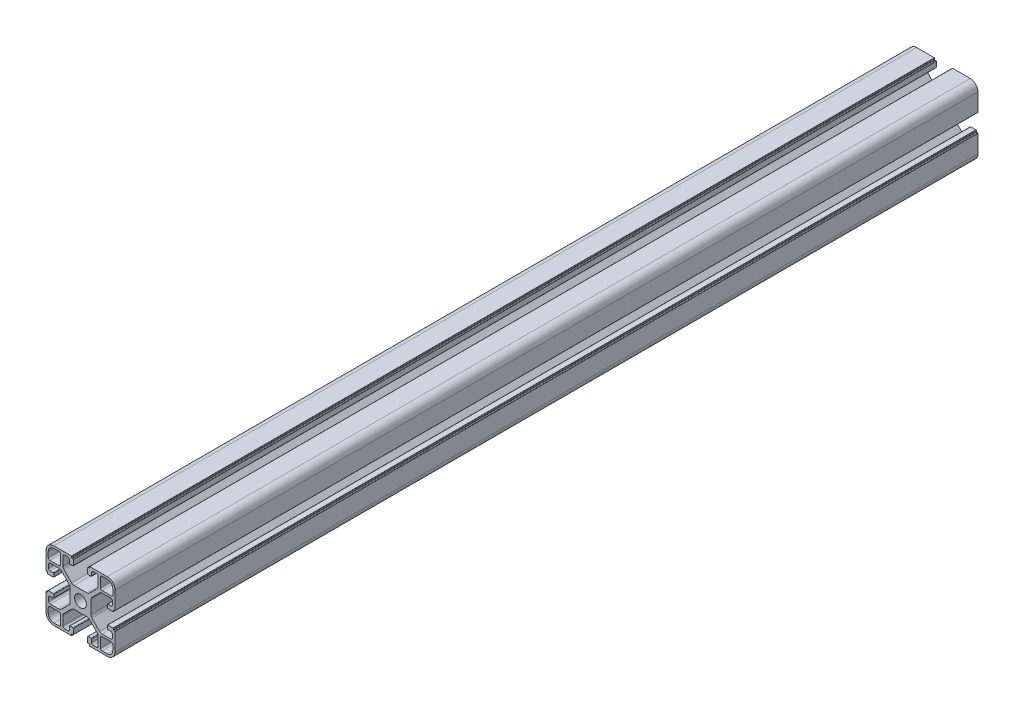
SolidWorks part; units mm, degrees
material "6063-T5"
ref_plane "Front Plane" through (0, 0, 0) normal (0, 0, 1) x (1, 0, 0)
ref_plane "Top Plane" through (0, 0, 0) normal (0, 1, 0) x (1, 0, 0)
ref_plane "Right Plane" through (0, 0, 0) normal (1, 0, 0) x (0, 0, -1)
sketch "Sketch2" plane through (0, 0, 0) normal (0, 0, 1) x (1, 0, 0)
  line L0 (4.5, 0) -> (14.7, 0)
  line L1 (40, 4.5) -> (40, 14.7)
  line L2 (35.5, 40) -> (25.3, 40)
  line L3 (0, 35.5) -> (0, 25.3)
  line L4 (15.9, 1.2) -> (15.9, 4.2)
  line L5 (24.1, 1.2) -> (24.1, 4.2)
  line L6 (38.8, 24.1) -> (35.8, 24.1)
  line L7 (35.5, 24.4) -> (35.5, 26.1)
  line L8 (14, 23.7574) -> (14, 16.2426)
  line L9 (16.2426, 14) -> (23.7574, 14)
  line L10 (26, 16.2426) -> (26, 23.7574)
  line L11 (13.4142, 14.8284) -> (8.9216, 10.3358)
  line L12 (23.7574, 26) -> (16.2426, 26)
  line L13 (4.5, 24.4) -> (4.5, 26.1)
  line L14 (1.2, 24.1) -> (4.2, 24.1)
  line L15 (15.9, 38.8) -> (15.9, 35.8)
  line L16 (14.8284, 26.5858) -> (10.3358, 31.0784)
  line L17 (13.4142, 25.1716) -> (8.9216, 29.6642)
  line L18 (14.8284, 13.4142) -> (10.3358, 8.9216)
  line L19 (25.1716, 13.4142) -> (29.6642, 8.9216)
  line L20 (26.5858, 14.8284) -> (31.0784, 10.3358)
  line L21 (26.5858, 25.1716) -> (31.0784, 29.6642)
  line L22 (25.1716, 26.5858) -> (29.6642, 31.0784)
  line L23 (24.1, 38.8) -> (24.1, 35.8)
  line L24 (14.7, 40) -> (4.5, 40)
  line L25 (25.3, 0) -> (35.5, 0)
  line L26 (38.8, 15.9) -> (35.8, 15.9)
  line L27 (40, 25.3) -> (40, 35.5)
  line L28 (1.2, 15.9) -> (4.2, 15.9)
  line L29 (0, 14.7) -> (0, 4.5)
  line L30 (4.5, 15.6) -> (4.5, 13.9)
  line L31 (35.5, 15.6) -> (35.5, 13.9)
  line L32 (15.6, 35.5) -> (13.9, 35.5)
  line L33 (24.4, 35.5) -> (26.1, 35.5)
  line L34 (15.6, 4.5) -> (13.9, 4.5)
  line L35 (24.4, 4.5) -> (26.1, 4.5)
  line L36 (12.6, 38.5) -> (10.75, 38.5)
  line L37 (1.5, 12.6) -> (1.5, 10.75)
  line L38 (27.4, 1.5) -> (29.25, 1.5)
  line L39 (38.5, 27.4) -> (38.5, 29.25)
  line L40 (38.5, 10.75) -> (38.5, 12.6)
  line L41 (29.25, 38.5) -> (27.4, 38.5)
  line L42 (1.5, 29.25) -> (1.5, 27.4)
  line L43 (10.75, 1.5) -> (12.6, 1.5)
  line L44 (35.8, 26.4) -> (37.5, 26.4)
  line L45 (35.8, 13.6) -> (37.5, 13.6)
  line L46 (4.2, 26.4) -> (2.5, 26.4)
  line L47 (13.6, 35.8) -> (13.6, 37.5)
  line L48 (26.4, 35.8) -> (26.4, 37.5)
  line L49 (4.2, 13.6) -> (2.5, 13.6)
  line L50 (13.6, 4.2) -> (13.6, 2.5)
  line L51 (26.4, 4.2) -> (26.4, 2.5)
  line L52 (9.75, 7.5074) -> (9.75, 2.5)
  line L53 (30.25, 7.5074) -> (30.25, 2.5)
  line L54 (9.75, 37.5) -> (9.75, 32.4926)
  line L55 (30.25, 37.5) -> (30.25, 32.4926)
  line L56 (32.4926, 30.25) -> (37.5, 30.25)
  line L57 (37.5, 9.75) -> (32.4926, 9.75)
  line L58 (2.5, 30.25) -> (7.5074, 30.25)
  line L59 (2.5, 9.75) -> (7.5074, 9.75)
  line L60 (31.55, 37.7) -> (31.55, 32.55)
  line L61 (32.55, 31.55) -> (37.7, 31.55)
  line L62 (1.3, 35.5) -> (1.3, 32.55)
  line L63 (4.5, 38.7) -> (7.45, 38.7)
  line L64 (32.55, 38.7) -> (35.5, 38.7)
  line L65 (38.7, 35.5) -> (38.7, 32.55)
  line L66 (8.45, 37.7) -> (8.45, 32.55)
  line L67 (2.3, 31.55) -> (7.45, 31.55)
  line L68 (1.3, 7.45) -> (1.3, 4.5)
  line L69 (2.3, 8.45) -> (7.45, 8.45)
  line L70 (8.45, 7.45) -> (8.45, 2.3)
  line L71 (4.5, 1.3) -> (7.45, 1.3)
  line L72 (31.55, 7.45) -> (31.55, 2.3)
  line L73 (32.55, 8.45) -> (37.7, 8.45)
  line L74 (38.7, 7.45) -> (38.7, 4.5)
  line L75 (32.55, 1.3) -> (35.5, 1.3)
  line L77 (14.9, 39.8) -> (14.9, 39.2)
  line L78 (15.1, 39) -> (15.7, 39)
  line L79 (25.1, 39.8) -> (25.1, 39.2)
  line L80 (24.9, 39) -> (24.3, 39)
  line L81 (25.1, 0.2) -> (25.1, 0.8)
  line L82 (24.9, 1) -> (24.3, 1)
  line L83 (14.9, 0.2) -> (14.9, 0.8)
  line L84 (15.1, 1) -> (15.7, 1)
  line L85 (0.2, 25.1) -> (0.8, 25.1)
  line L86 (1, 24.9) -> (1, 24.3)
  line L87 (0.2, 14.9) -> (0.8, 14.9)
  line L88 (1, 15.1) -> (1, 15.7)
  line L89 (39.8, 25.1) -> (39.2, 25.1)
  line L90 (39, 24.9) -> (39, 24.3)
  line L91 (39, 15.7) -> (39, 15.1)
  line L92 (39.2, 14.9) -> (39.8, 14.9)
  circle A0 centre (20, 20) radius 3.4
  arc A1 (1.3, 35.5) -> (4.5, 38.7) centre (4.5, 35.5) cw
  arc A2 (1.3, 4.5) -> (4.5, 1.3) centre (4.5, 4.5) ccw
  arc A3 (38.7, 4.5) -> (35.5, 1.3) centre (35.5, 4.5) cw
  arc A4 (35.5, 38.7) -> (38.7, 35.5) centre (35.5, 35.5) cw
  arc A5 (40, 35.5) -> (35.5, 40) centre (35.5, 35.5) ccw
  arc A6 (35.5, 0) -> (40, 4.5) centre (35.5, 4.5) ccw
  arc A7 (4.5, 0) -> (0, 4.5) centre (4.5, 4.5) cw
  arc A8 (4.5, 40) -> (0, 35.5) centre (4.5, 35.5) ccw
  arc A9 (13.4142, 14.8284) -> (14, 16.2426) centre (12, 16.2426) ccw
  arc A10 (7.5074, 9.75) -> (8.9216, 10.3358) centre (7.5074, 11.75) ccw
  arc A11 (9.75, 7.5074) -> (10.3358, 8.9216) centre (11.75, 7.5074) cw
  arc A12 (30.25, 7.5074) -> (29.6642, 8.9216) centre (28.25, 7.5074) ccw
  arc A13 (14.8284, 13.4142) -> (16.2426, 14) centre (16.2426, 12) cw
  arc A14 (25.1716, 13.4142) -> (23.7574, 14) centre (23.7574, 12) ccw
  arc A15 (32.4926, 9.75) -> (31.0784, 10.3358) centre (32.4926, 11.75) cw
  arc A16 (26.5858, 14.8284) -> (26, 16.2426) centre (28, 16.2426) cw
  arc A17 (32.4926, 30.25) -> (31.0784, 29.6642) centre (32.4926, 28.25) ccw
  arc A18 (26.5858, 25.1716) -> (26, 23.7574) centre (28, 23.7574) ccw
  arc A19 (13.4142, 25.1716) -> (14, 23.7574) centre (12, 23.7574) cw
  arc A20 (7.5074, 30.25) -> (8.9216, 29.6642) centre (7.5074, 28.25) cw
  arc A21 (9.75, 32.4926) -> (10.3358, 31.0784) centre (11.75, 32.4926) ccw
  arc A22 (30.25, 32.4926) -> (29.6642, 31.0784) centre (28.25, 32.4926) cw
  arc A23 (25.1716, 26.5858) -> (23.7574, 26) centre (23.7574, 28) cw
  arc A24 (14.8284, 26.5858) -> (16.2426, 26) centre (16.2426, 28) ccw
  arc A25 (37.7, 8.45) -> (38.7, 7.45) centre (37.7, 7.45) cw
  arc A26 (31.55, 2.3) -> (32.55, 1.3) centre (32.55, 2.3) ccw
  arc A27 (31.55, 7.45) -> (32.55, 8.45) centre (32.55, 7.45) cw
  arc A28 (8.45, 2.3) -> (7.45, 1.3) centre (7.45, 2.3) cw
  arc A29 (1.3, 7.45) -> (2.3, 8.45) centre (2.3, 7.45) cw
  arc A30 (7.45, 8.45) -> (8.45, 7.45) centre (7.45, 7.45) cw
  arc A31 (38.7, 32.55) -> (37.7, 31.55) centre (37.7, 32.55) cw
  arc A32 (31.55, 32.55) -> (32.55, 31.55) centre (32.55, 32.55) ccw
  arc A33 (31.55, 37.7) -> (32.55, 38.7) centre (32.55, 37.7) cw
  arc A34 (7.45, 38.7) -> (8.45, 37.7) centre (7.45, 37.7) cw
  arc A35 (8.45, 32.55) -> (7.45, 31.55) centre (7.45, 32.55) cw
  arc A36 (1.3, 32.55) -> (2.3, 31.55) centre (2.3, 32.55) ccw
  arc A37 (30.25, 2.5) -> (29.25, 1.5) centre (29.25, 2.5) cw
  arc A38 (26.4, 2.5) -> (27.4, 1.5) centre (27.4, 2.5) ccw
  arc A39 (13.6, 2.5) -> (12.6, 1.5) centre (12.6, 2.5) cw
  arc A40 (9.75, 2.5) -> (10.75, 1.5) centre (10.75, 2.5) ccw
  arc A41 (26.4, 37.5) -> (27.4, 38.5) centre (27.4, 37.5) cw
  arc A42 (30.25, 37.5) -> (29.25, 38.5) centre (29.25, 37.5) ccw
  arc A43 (37.5, 26.4) -> (38.5, 27.4) centre (37.5, 27.4) ccw
  arc A44 (37.5, 30.25) -> (38.5, 29.25) centre (37.5, 29.25) cw
  arc A45 (37.5, 13.6) -> (38.5, 12.6) centre (37.5, 12.6) cw
  arc A46 (37.5, 9.75) -> (38.5, 10.75) centre (37.5, 10.75) ccw
  arc A47 (2.5, 9.75) -> (1.5, 10.75) centre (2.5, 10.75) cw
  arc A48 (2.5, 13.6) -> (1.5, 12.6) centre (2.5, 12.6) ccw
  arc A49 (2.5, 26.4) -> (1.5, 27.4) centre (2.5, 27.4) cw
  arc A50 (2.5, 30.25) -> (1.5, 29.25) centre (2.5, 29.25) ccw
  arc A51 (9.75, 37.5) -> (10.75, 38.5) centre (10.75, 37.5) cw
  arc A52 (13.6, 37.5) -> (12.6, 38.5) centre (12.6, 37.5) ccw
  arc A53 (26.1, 35.5) -> (26.4, 35.8) centre (26.1, 35.8) ccw
  arc A54 (24.1, 35.8) -> (24.4, 35.5) centre (24.4, 35.8) ccw
  arc A55 (15.9, 35.8) -> (15.6, 35.5) centre (15.6, 35.8) cw
  arc A56 (13.9, 35.5) -> (13.6, 35.8) centre (13.9, 35.8) cw
  arc A57 (13.9, 4.5) -> (13.6, 4.2) centre (13.9, 4.2) ccw
  arc A58 (15.9, 4.2) -> (15.6, 4.5) centre (15.6, 4.2) ccw
  arc A59 (24.1, 4.2) -> (24.4, 4.5) centre (24.4, 4.2) cw
  arc A60 (26.1, 4.5) -> (26.4, 4.2) centre (26.1, 4.2) cw
  arc A61 (35.5, 13.9) -> (35.8, 13.6) centre (35.8, 13.9) ccw
  arc A62 (35.8, 15.9) -> (35.5, 15.6) centre (35.8, 15.6) ccw
  arc A63 (35.8, 24.1) -> (35.5, 24.4) centre (35.8, 24.4) cw
  arc A64 (35.5, 26.1) -> (35.8, 26.4) centre (35.8, 26.1) cw
  arc A65 (4.5, 13.9) -> (4.2, 13.6) centre (4.2, 13.9) cw
  arc A66 (4.2, 15.9) -> (4.5, 15.6) centre (4.2, 15.6) cw
  arc A67 (4.2, 24.1) -> (4.5, 24.4) centre (4.2, 24.4) ccw
  arc A68 (4.5, 26.1) -> (4.2, 26.4) centre (4.2, 26.1) ccw
  arc A69 (25.3, 0) -> (25.1, 0.2) centre (25.3, 0.2) cw
  arc A70 (25.1, 0.8) -> (24.9, 1) centre (24.9, 0.8) ccw
  arc A71 (24.3, 1) -> (24.1, 1.2) centre (24.3, 1.2) cw
  arc A72 (14.7, 0) -> (14.9, 0.2) centre (14.7, 0.2) ccw
  arc A73 (14.9, 0.8) -> (15.1, 1) centre (15.1, 0.8) cw
  arc A74 (15.7, 1) -> (15.9, 1.2) centre (15.7, 1.2) ccw
  arc A75 (39.8, 14.9) -> (40, 14.7) centre (39.8, 14.7) cw
  arc A76 (39, 15.1) -> (39.2, 14.9) centre (39.2, 15.1) ccw
  arc A77 (38.8, 15.9) -> (39, 15.7) centre (38.8, 15.7) cw
  arc A78 (0, 25.3) -> (0.2, 25.1) centre (0.2, 25.3) ccw
  arc A79 (0.8, 25.1) -> (1, 24.9) centre (0.8, 24.9) cw
  arc A80 (1, 24.3) -> (1.2, 24.1) centre (1.2, 24.3) ccw
  arc A81 (0, 14.7) -> (0.2, 14.9) centre (0.2, 14.7) cw
  arc A82 (0.8, 14.9) -> (1, 15.1) centre (0.8, 15.1) ccw
  arc A83 (1, 15.7) -> (1.2, 15.9) centre (1.2, 15.7) cw
  arc A84 (39, 24.3) -> (38.8, 24.1) centre (38.8, 24.3) cw
  arc A85 (39.2, 25.1) -> (39, 24.9) centre (39.2, 24.9) ccw
  arc A86 (40, 25.3) -> (39.8, 25.1) centre (39.8, 25.3) cw
  arc A87 (24.3, 39) -> (24.1, 38.8) centre (24.3, 38.8) ccw
  arc A88 (25.1, 39.2) -> (24.9, 39) centre (24.9, 39.2) cw
  arc A89 (25.3, 40) -> (25.1, 39.8) centre (25.3, 39.8) ccw
  arc A90 (14.9, 39.2) -> (15.1, 39) centre (15.1, 39.2) ccw
  arc A91 (15.7, 39) -> (15.9, 38.8) centre (15.7, 38.8) cw
  arc A92 (14.7, 40) -> (14.9, 39.8) centre (14.7, 39.8) cw
  point P93 (0, 0)
extrude "Boss-Extrude1" add sketch "Sketch2" along normal blind 500
